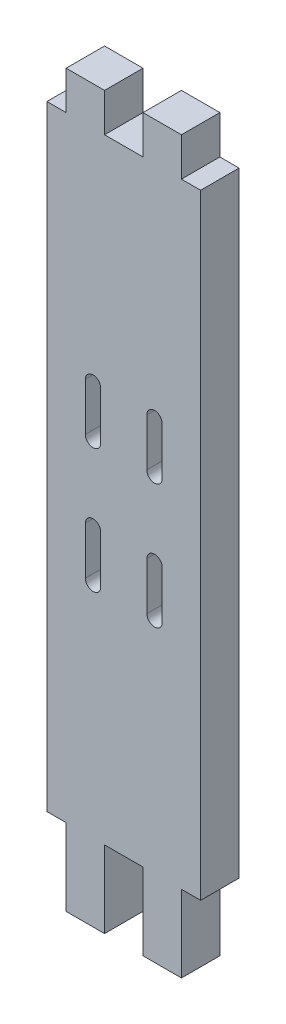
SolidWorks part; units mm, degrees
ref_plane "Front Plane" through (0, 0, 0) normal (0, 0, 1) x (1, 0, 0)
ref_plane "Top Plane" through (0, 0, 0) normal (0, 1, 0) x (1, 0, 0)
ref_plane "Right Plane" through (0, 0, 0) normal (1, 0, 0) x (0, 0, -1)
sketch "Sketch1" plane through (0, 0, 0) normal (0, 0, 1) x (1, 0, 0)
  line L0 (-7.5, 40) -> (-7.5, 45)
  line L1 (-10, -40) -> (-7.5, -40)
  line L2 (-10, -40) -> (-10, 40)
  line L3 (-10, 40) -> (-7.5, 40)
  line L4 (10, -40) -> (10, 40)
  line L5 (-10, -40) -> (10, 40) construction
  line L6 (-10, 40) -> (10, -40) construction
  line L7 (-7.5, 45) -> (-2.5, 45)
  line L8 (-2.5, 45) -> (-2.5, 40)
  line L9 (2.5, 40) -> (2.5, 45)
  line L10 (2.5, 45) -> (7.5, 45)
  line L11 (7.5, 45) -> (7.5, 40)
  line L12 (-2.5, 40) -> (2.5, 40)
  line L13 (7.5, 40) -> (10, 40)
  line L14 (-2.5, -40) -> (2.5, -40)
  line L16 (-7.5, -40) -> (-7.5, -45)
  line L20 (2.5, -40) -> (2.5, -45)
  line L23 (7.5, -40) -> (10, -40)
  line L24 (-7.5, -45) -> (-7.5, -50)
  line L25 (-7.5, -50) -> (-2.5, -50)
  line L26 (-2.5, -50) -> (-2.5, -40)
  line L27 (2.5, -45) -> (2.5, -50)
  line L28 (2.5, -50) -> (7.5, -50)
  line L29 (7.5, -50) -> (7.5, -40)
  line L30 (0, 0) -> (0, 44.2491) construction
  line L31 (0, 0) -> (41.6146, 0) construction
  line L32 (4, -11.2) -> (4, -5) construction
  line L35 (3, -11.2) -> (3, -5)
  line L38 (5, -11.2) -> (5, -5)
  line L41 (4, 11.2) -> (4, 5) construction
  line L44 (3, 11.2) -> (3, 5)
  line L51 (5, 11.2) -> (5, 5)
  line L52 (-4, 11.2) -> (-4, 5) construction
  line L53 (-3, 11.2) -> (-3, 5)
  line L54 (-5, 11.2) -> (-5, 5)
  line L55 (-4, -11.2) -> (-4, -5) construction
  line L56 (-3, -11.2) -> (-3, -5)
  line L57 (-5, -11.2) -> (-5, -5)
  arc A29 (3, -11.2) -> (5, -11.2) centre (4, -11.2) ccw
  arc A30 (5, -5) -> (3, -5) centre (4, -5) ccw
  arc A33 (3, 11.2) -> (5, 11.2) centre (4, 11.2) cw
  arc A34 (5, 5) -> (3, 5) centre (4, 5) cw
  arc A35 (-3, 11.2) -> (-5, 11.2) centre (-4, 11.2) ccw
  arc A36 (-5, 5) -> (-3, 5) centre (-4, 5) ccw
  arc A37 (-3, -11.2) -> (-5, -11.2) centre (-4, -11.2) cw
  arc A38 (-5, -5) -> (-3, -5) centre (-4, -5) cw
  point P0 (0, 0)
  point P29 (4, -8.1)
  point P36 (4, 8.1)
  point P45 (-4, 8.1)
  point P52 (-4, -8.1)
  dimension "D8" = 1
  dimension "D9" = 6.2
  dimension "D1" = 5
  dimension "D2" = 5
  dimension "D3" = 20
  dimension "D4" = 5
  dimension "D5" = 80
  dimension "D6" = 5
  dimension "D7" = 10
  dimension "D10" = 4
  dimension "D11" = 8.1
extrude "Boss-Extrude1" add sketch "Sketch1" along normal blind 5
